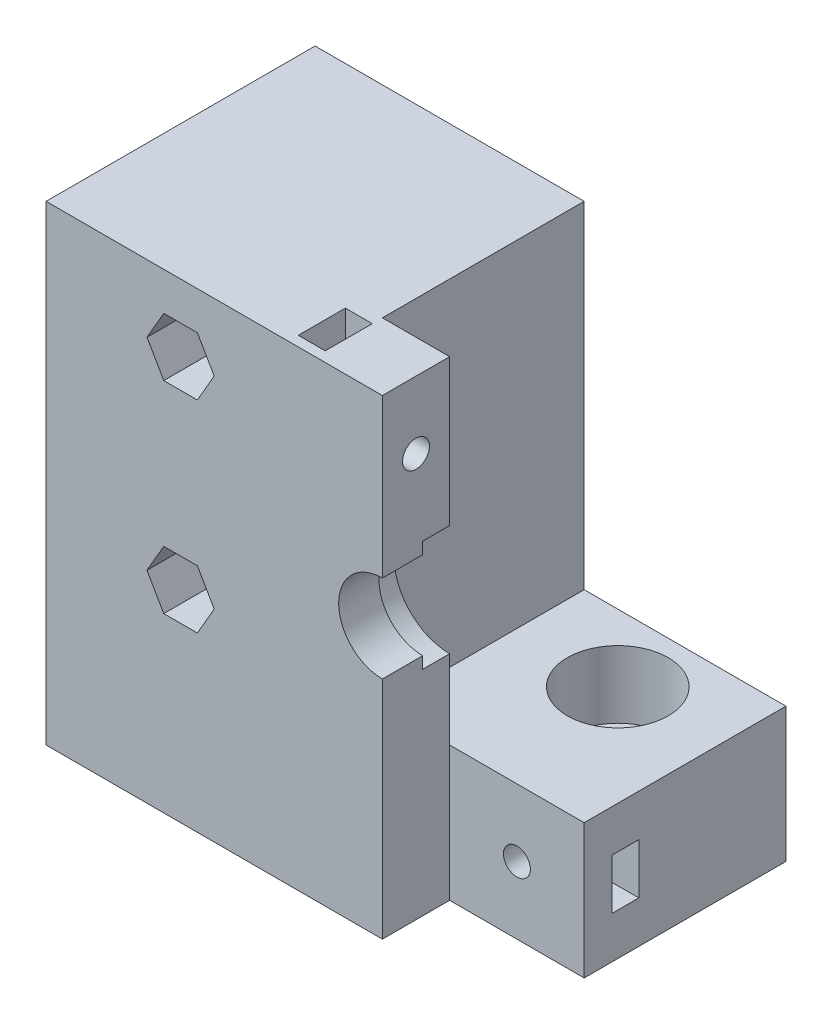
SolidWorks part; units mm, degrees
ref_plane "Front Plane" through (0, 0, 0) normal (0, 0, 1) x (1, 0, 0)
ref_plane "Top Plane" through (0, 0, 0) normal (0, 1, 0) x (1, 0, 0)
ref_plane "Right Plane" through (0, 0, 0) normal (1, 0, 0) x (0, 0, -1)
sketch "Sketch1" plane through (0, 0, 0) normal (0, 1, 0) x (1, 0, 0)
  line L0 (0, 0) -> (0, 30)
  line L1 (0, 0) -> (70, 0)
  line L2 (70, 0) -> (70, 105)
  line L3 (70, 105) -> (40, 105)
  line L4 (0, 30) -> (40, 30)
  line L5 (40, 30) -> (40, 105)
  circle A0 centre (55, 76) radius 4.5
  circle A1 centre (55, 20) radius 4.5
  circle A2 centre (20, 20) radius 7.5
  dimension "D5" = 9
  dimension "D8" = 15
  dimension "D10" = 9
  dimension "D1" = 30
  dimension "D2" = 70
  dimension "D3" = 105
  dimension "D4" = 30
  dimension "D6" = 29
  dimension "D7" = 56
  dimension "D9" = 35
extrude "Boss-Extrude1" add sketch "Sketch1" along normal blind 20
sketch "Sketch3" plane through (0, 20, 0) normal (0, 1, 0) x (1, 0, 0)
  line L0 (0, 0) -> (70, 0) construction
  line L1 (0, 30) -> (40, 30)
  line L2 (0, 30) -> (0, 0)
  line L3 (0, 0) -> (40, 0)
  line L4 (40, 30) -> (40, 0)
extrude "Boss-Extrude2" add sketch "Sketch3" along normal blind 50
sketch "Sketch4" plane through (0, 0, 0) normal (0, 0, 1) x (1, 0, 0)
  line L1 (40, 70) -> (40, 20) construction
  line L2 (0, 70) -> (40, 70) construction
  circle A0 centre (20, 30) radius 2
  circle A1 centre (20, 60) radius 2
  dimension "D1" = 4
  dimension "D2" = 4
  dimension "D3" = 20
  dimension "D4" = 10
  dimension "D5" = 30
  dimension "D6" = 0
extrude "Cut-Extrude1" cut sketch "Sketch4" against normal blind 50
sketch "Sketch5" plane through (0, 0, 0) normal (0, 0, 1) x (1, 0, 0)
  line L1 (0, 70) -> (40, 70)
  line L2 (0, 70) -> (0, 0)
  line L3 (0, 0) -> (40, 0)
  line L4 (40, 70) -> (40, 0)
extrude "Boss-Extrude3" add sketch "Sketch5" along normal blind 10
sketch "Sketch6" plane through (40, 0, 0) normal (1, 0, 0) x (0, 0, -1)
  line L1 (-10, 70) -> (0, 70)
  line L2 (-10, 70) -> (-10, 0)
  line L3 (-10, 0) -> (0, 0)
  line L4 (0, 70) -> (0, 0)
extrude "Boss-Extrude4" add sketch "Sketch6" along normal blind 10
sketch "Sketch7" plane through (0, 0, 10) normal (0, 0, 1) x (1, 0, 0)
  line L0 (50, 70) -> (50, 0) construction
  circle A0 centre (50, 40) radius 6.5
  dimension "D2" = 13
  dimension "D1" = 30
extrude "Cut-Extrude2" cut sketch "Sketch7" against normal blind 10
sketch "Sketch8" plane through (0, 0, 0) normal (0, 0, -1) x (-1, 0, 0)
  circle A0 centre (-50, 40) radius 8.25
  dimension "D1" = 16.5
extrude "Cut-Extrude3" cut sketch "Sketch8" against normal blind 4
sketch "Sketch9" plane through (0, 0, 0) normal (0, 0, 1) x (1, 0, 0)
  circle A0 centre (60, 10) radius 2
  dimension "D1" = 4
extrude "Cut-Extrude4" cut sketch "Sketch9" against normal blind 10
sketch "Sketch10" plane through (50, 0, 0) normal (1, 0, 0) x (0, 0, -1)
  line L0 (0, 70) -> (-10, 70) construction
  circle A0 centre (-5, 60) radius 2
  point P4 (-5, 70)
  dimension "D2" = 4
  dimension "D1" = 0
  dimension "D3" = 10
extrude "Cut-Extrude5" cut sketch "Sketch10" against normal blind 10
sketch "Sketch11" plane through (0, 0, 10) normal (0, 0, 1) x (1, 0, 0)
  line L1 (15, 60) -> (17.5, 55.6699)
  line L2 (17.5, 55.6699) -> (22.5, 55.6699)
  line L3 (22.5, 55.6699) -> (25, 60)
  line L4 (25, 60) -> (22.5, 64.3301)
  line L5 (22.5, 64.3301) -> (17.5, 64.3301)
  line L6 (17.5, 64.3301) -> (15, 60)
  line L7 (15, 30) -> (17.5, 25.6699)
  line L8 (17.5, 25.6699) -> (22.5, 25.6699)
  line L9 (22.5, 25.6699) -> (25, 30)
  line L10 (25, 30) -> (22.5, 34.3301)
  line L11 (22.5, 34.3301) -> (17.5, 34.3301)
  line L12 (17.5, 34.3301) -> (15, 30)
  circle A0 centre (20, 60) radius 4.3301 construction
  circle A1 centre (20, 30) radius 4.3301 construction
  point P1 (16.25, 57.8349)
  dimension "D1" = 2.5
  dimension "D2" = 5
extrude "Cut-Extrude6" cut sketch "Sketch11" against normal blind 30
sketch "Sketch12" plane through (70, 0, 0) normal (1, 0, 0) x (0, 0, -1)
  line L0 (0, 20) -> (0, 0) construction
  line L1 (8.1322, 13.75) -> (4.1322, 13.75)
  line L2 (8.1322, 13.75) -> (8.1322, 6.25)
  line L3 (8.1322, 6.25) -> (4.1322, 6.25)
  line L4 (4.1322, 13.75) -> (4.1322, 6.25)
  point P4 (4.1322, 10)
  point P7 (0, 10)
  dimension "D1" = 7.5
  dimension "D2" = 0
  dimension "D3" = 4
extrude "Cut-Extrude7" cut sketch "Sketch12" against normal blind 20
sketch "Sketch13" plane through (0, 70, 0) normal (0, 1, 0) x (1, 0, 0)
  line L0 (50, 0) -> (50, -10) construction
  line L1 (40, -1.5) -> (36, -1.5)
  line L2 (40, -1.5) -> (40, -8.5)
  line L3 (40, -8.5) -> (36, -8.5)
  line L4 (36, -1.5) -> (36, -8.5)
  point P4 (40, -5)
  point P7 (50, -5)
  point P8 (38, -8.5)
  dimension "D1" = 4
  dimension "D2" = 7
  dimension "D3" = 0
  dimension "D4" = 12
extrude "Cut-Extrude8" cut sketch "Sketch13" against normal blind 16
sketch "Sketch14" plane through (0, 20, 0) normal (0, 1, 0) x (1, 0, 0)
  circle A0 centre (55, 20) radius 7.5
  circle A1 centre (55, 76) radius 7.5
  dimension "D1" = 15
  dimension "D2" = 15
extrude "Cut-Extrude9" cut sketch "Sketch14" against normal blind 10
fillet "Fillet2" radius 15 2 edges at (40, 10, -30) (40, 45, -30)
sketch "Sketch15" plane through (40, 0, 0) normal (1, 0, 0) x (0, 0, -1)
  line L1 (30, 70) -> (45, 70)
  line L2 (30, 70) -> (30, 20)
  line L3 (30, 20) -> (45, 20)
  line L4 (45, 70) -> (45, 20)
extrude "Cut-Extrude10" cut sketch "Sketch15" against normal blind 20
sketch "Sketch16" plane through (0, 0, -105) normal (0, 0, -1) x (-1, 0, 0)
  line L1 (-40, 20) -> (-40, 0) construction
  line L2 (-70, 20) -> (-40, 20)
  line L3 (-70, 20) -> (-70, 15)
  line L4 (-70, 15) -> (-40, 15)
  line L5 (-40, 20) -> (-40, 15)
  dimension "D1" = 5
extrude "Cut-Extrude11" cut sketch "Sketch16" against normal blind 11
sketch "Sketch17" plane through (0, 15, 0) normal (0, 1, 0) x (1, 0, 0)
  line L0 (70, 94) -> (40, 94) construction
  line L1 (59, 94) -> (51, 94)
  line L2 (59, 94) -> (59, 100)
  line L3 (59, 100) -> (51, 100)
  line L4 (51, 94) -> (51, 100)
  line L6 (70, 105) -> (40, 105) construction
  point P6 (55, 100)
  point P9 (55, 105)
  dimension "D1" = 6
  dimension "D2" = 8
  dimension "D3" = 0
extrude "Cut-Extrude12" cut sketch "Sketch17" against normal blind 20
sketch "Sketch20" plane through (0, 20, 0) normal (0, 1, 0) x (1, 0, 0)
  line L1 (25, 30) -> (86.1474, 30)
  line L2 (25, 30) -> (25, 116.9242)
  line L3 (25, 116.9242) -> (86.1474, 116.9242)
  line L4 (86.1474, 30) -> (86.1474, 116.9242)
extrude "Cut-Extrude14" cut sketch "Sketch20" against normal blind 50
